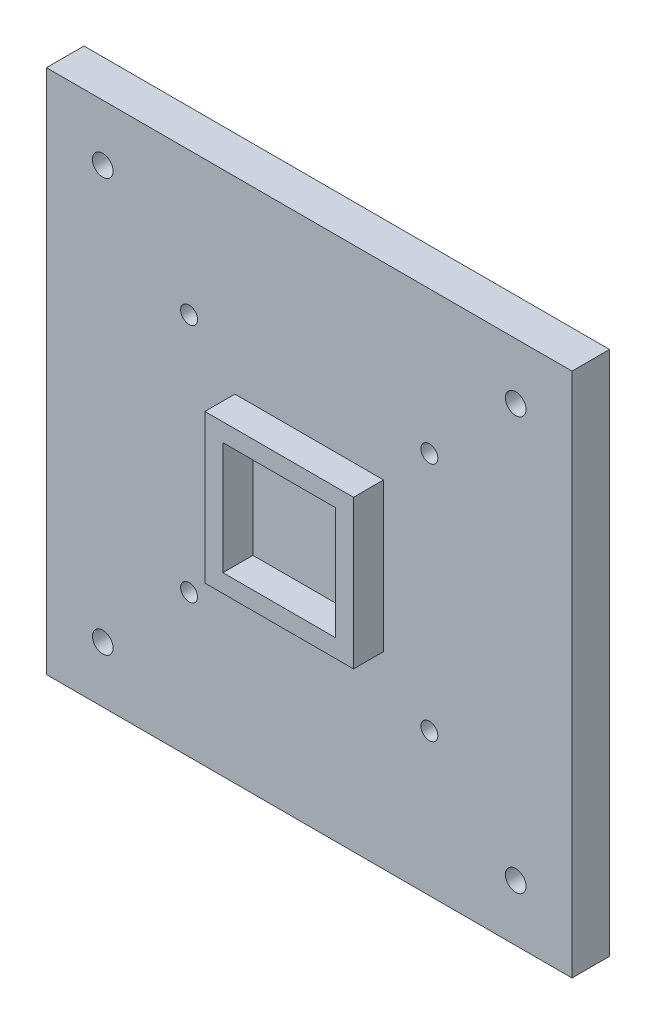
SolidWorks part; units mm, degrees
ref_plane "前视基准面" through (0, 0, 0) normal (0, 0, 1) x (1, 0, 0)
ref_plane "上视基准面" through (0, 0, 0) normal (0, 1, 0) x (1, 0, 0)
ref_plane "右视基准面" through (0, 0, 0) normal (1, 0, 0) x (0, 0, -1)
other "Configuration Table"
sketch "草图1" plane through (0, 0, 0) normal (0, 0, 1) x (1, 0, 0)
  line L1 (-70, -70) -> (70, -70)
  line L2 (-70, -70) -> (-70, 70)
  line L3 (-70, 70) -> (70, 70)
  line L4 (70, -70) -> (70, 70)
extrude "锚固底板140x140" add sketch "草图1" along normal blind 10
sketch "草图2" plane through (0, 0, 0) normal (0, 0, 1) x (1, 0, 0)
  line L1 (-19.8, -19.8) -> (19.8, -19.8)
  line L2 (-19.8, -19.8) -> (-19.8, 19.8)
  line L3 (-19.8, 19.8) -> (19.8, 19.8)
  line L4 (19.8, -19.8) -> (19.8, 19.8)
  line L6 (-15, -15) -> (15, -15)
  line L7 (-15, -15) -> (-15, 15)
  line L8 (-15, 15) -> (15, 15)
  line L9 (15, -15) -> (15, 15)
extrude "立柱定位凸台39p6" add sketch "草图2" along normal blind 8 from offset 10
sketch "草图3" plane through (0, 0, 0) normal (0, 0, 1) x (1, 0, 0)
  circle A0 centre (-55, -55) radius 2.75
  circle A1 centre (-55, 55) radius 2.75
  circle A2 centre (55, -55) radius 2.75
  circle A3 centre (55, 55) radius 2.75
  circle A4 centre (-32, -32) radius 2.25
  circle A5 centre (-32, 32) radius 2.25
  circle A6 centre (32, -32) radius 2.25
  circle A7 centre (32, 32) radius 2.25
extrude "桌面M5与立柱M4通孔" cut sketch "草图3" against normal through all and the other way through all
